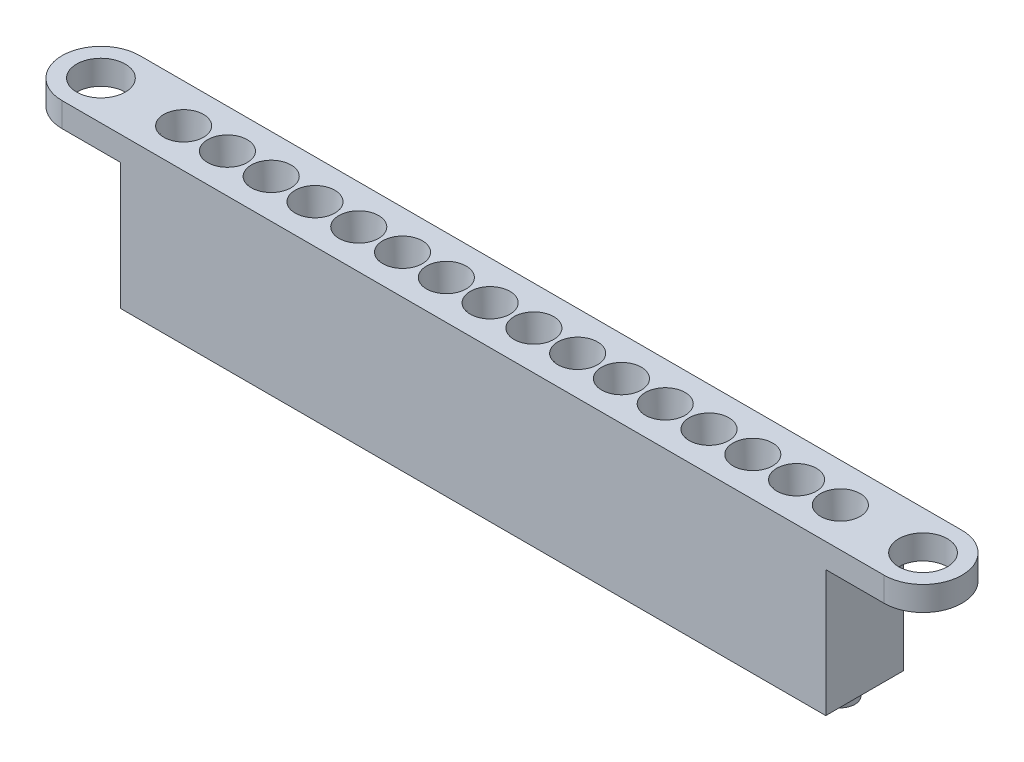
SolidWorks part; units mm, degrees
material "AISI 316 Stainless Steel Sheet (SS)"
ref_plane "Front" through (0, 0, 0) normal (0, 0, 1) x (1, 0, 0)
ref_plane "Top" through (0, 0, 0) normal (0, 1, 0) x (1, 0, 0)
ref_plane "Right" through (0, 0, 0) normal (1, 0, 0) x (0, 0, -1)
sketch "Sketch43" plane through (0, 0, 0) normal (0, 1, 0) x (1, 0, 0)
  line L0 (42.25, 0) -> (-42.25, 0) construction
  line L1 (42.25, -4) -> (-42.25, -4)
  line L2 (42.25, 4) -> (-42.25, 4)
  arc A0 (42.25, -4) -> (42.25, 4) centre (42.25, 0) ccw
  arc A1 (-42.25, 4) -> (-42.25, -4) centre (-42.25, 0) ccw
  circle A2 centre (-42.25, 0) radius 2.5
  circle A3 centre (42.25, 0) radius 2.5
  point P2 (0, 0)
  dimension "D3" = 5
  dimension "D1" = 84.5
  dimension "D2" = 8
extrude "Boss-Extrude6" add sketch "Sketch43" along normal blind 17
sketch "Sketch41" plane through (0, 0, 0) normal (0, 0, 1) x (1, 0, 0)
  line L0 (0, 2.2756) -> (0, 5.0724) construction
  line L1 (2.25, 0) -> (2.25, 17) construction
  line L2 (2.25, 0) -> (3.25, 0) construction
  line L3 (3.25, 0) -> (4.2898, 17)
  line L4 (4.2898, 17) -> (4.7898, 17) construction
  line L5 (4.7898, 17) -> (3.75, 0) construction
  line L6 (3.75, 0) -> (3.25, 0) construction
  line L7 (4.2898, 17) -> (2.25, 17)
  line L8 (2.25, 17) -> (2.25, 0)
  line L9 (2.25, 0) -> (3.25, 0)
  line L10 (-42.25, 17) -> (42.25, 17) construction
  dimension "D1" = 2.25
  dimension "D2" = 2
  dimension "D3" = 3
  dimension "D4" = 3.5
revolve "Cut-Revolve1" cut sketch "Sketch41" angle 360 about L8
pattern_linear "LPattern3" count 8 spacing 4.5 along (1, 0, 0) count 9 spacing 4.5 along (-1, 0, 0) of "Cut-Revolve1"
sketch "Sketch44" plane through (0, 0, 0) normal (0, 0, 1) x (1, 0, 0)
  line L0 (-42.25, 0) -> (42.25, 0) construction
  line L1 (-46.25, 14.5) -> (-36.25, 14.5)
  line L2 (-46.25, 14.5) -> (-46.25, 0)
  line L3 (-46.25, 0) -> (-36.25, 0)
  line L4 (-36.25, 14.5) -> (-36.25, 0)
  line L5 (-46.25, 17) -> (-46.25, 0) construction
  line L6 (-42.25, 17) -> (42.25, 17) construction
  line L7 (-39.75, 17) -> (-44.75, 17) construction
  line L8 (-39.75, 17) -> (-44.75, 17) construction
  line L9 (0, -4.7141) -> (0, -12.6187) construction
  line L10 (39.75, 17) -> (44.75, 17) construction
  line L11 (36.25, 14.5) -> (36.25, 0)
  line L12 (46.25, 0) -> (36.25, 0)
  line L13 (46.25, 14.5) -> (46.25, 0)
  line L14 (46.25, 14.5) -> (36.25, 14.5)
  point P12 (-42.25, 17)
  dimension "D1" = 2.5
  dimension "D2" = 6
extrude "Cut-Extrude13" cut sketch "Sketch44" against normal through all both and the other way through all
sketch "Sketch46" plane through (0, 0, 0) normal (0, 0, 1) x (1, 0, 0)
  line L0 (3.75, 0) -> (3.8417, 1.5)
  line L1 (4.7898, 17) -> (3.75, 0) construction
  line L2 (3.8417, 1.5) -> (4.25, 1.5)
  line L3 (4.25, 1.5) -> (4.25, 0)
  line L4 (-36.25, 0) -> (36.25, 0) construction
  line L5 (4.25, 0) -> (3.75, 0)
  line L6 (2.25, 17) -> (2.25, 0) construction
  line L7 (2.25, 17) -> (2.25, 0) construction
  dimension "D1" = 1.5
  dimension "D2" = 0.5
  dimension "D3" = 3.5
revolve "Cut-Revolve2" cut sketch "Sketch46" angle 360 about L7
pattern_linear "LPattern7" count 8 spacing 4.5 along (1, 0, 0) count 9 spacing 4.5 along (-1, 0, 0) of "Cut-Revolve2"
sketch "Sketch47" plane through (0, 0, 0) normal (0, 1, 0) x (1, 0, 0)
  line L0 (-36.25, 4) -> (-36.25, -4) construction
  line L1 (36.25, 4) -> (-36.25, 4) construction
  line L2 (36.25, 4) -> (36.25, -4) construction
  line L3 (-36.25, -4) -> (36.25, -4) construction
  line L4 (-36.25, 4) -> (-36.25, -4)
  line L5 (36.25, 4) -> (-36.25, 4)
  line L6 (36.25, 4) -> (36.25, -4)
  line L7 (-36.25, -4) -> (36.25, -4)
  circle A0 centre (-15.75, 0) radius 2 construction
  circle A1 centre (-20.25, 0) radius 2 construction
  circle A2 centre (-24.75, 0) radius 2 construction
  circle A3 centre (-29.25, 0) radius 2 construction
  circle A4 centre (-33.75, 0) radius 2 construction
  circle A5 centre (-15.75, 0) radius 2
  circle A6 centre (-20.25, 0) radius 2
  circle A7 centre (-24.75, 0) radius 2
  circle A8 centre (-29.25, 0) radius 2
  circle A9 centre (-33.75, 0) radius 2
  circle A10 centre (11.25, 0) radius 2 construction
  circle A11 centre (6.75, 0) radius 2 construction
  circle A12 centre (2.25, 0) radius 2 construction
  circle A13 centre (-2.25, 0) radius 2 construction
  circle A14 centre (-6.75, 0) radius 2 construction
  circle A15 centre (-11.25, 0) radius 2 construction
  circle A16 centre (11.25, 0) radius 2
  circle A17 centre (6.75, 0) radius 2
  circle A18 centre (2.25, 0) radius 2
  circle A19 centre (-2.25, 0) radius 2
  circle A20 centre (-6.75, 0) radius 2
  circle A21 centre (-11.25, 0) radius 2
  circle A22 centre (33.75, 0) radius 2 construction
  circle A23 centre (29.25, 0) radius 2 construction
  circle A24 centre (24.75, 0) radius 2 construction
  circle A25 centre (20.25, 0) radius 2 construction
  circle A26 centre (15.75, 0) radius 2 construction
  circle A27 centre (33.75, 0) radius 2
  circle A28 centre (29.25, 0) radius 2
  circle A29 centre (24.75, 0) radius 2
  circle A30 centre (20.25, 0) radius 2
  circle A31 centre (15.75, 0) radius 2
extrude "Cut-Extrude14" cut sketch "Sketch47" along normal up to surface (1.5 mm away) up to face at (-3.8417, 1.5, 0)
sketch "Sketch42" plane through (0, 0, 0) normal (0, 0, 1) x (1, 0, 0)
  line L0 (2.25, 0) -> (2.25, 17) construction
  line L1 (2.25, 0) -> (2.25, 17) construction
  line L2 (3.25, 0) -> (4.2898, 17) construction
  line L3 (3.25, 0) -> (4.2898, 17)
  line L4 (3.25, 0) -> (2.25, 0)
  line L5 (2.25, 17) -> (4.2898, 17)
  line L6 (2.25, 0) -> (2.25, 17)
revolve "Well Volume" [suppressed] add sketch "Sketch42" angle 360 about L1
sketch "stock" plane through (0, 0, 0) normal (0, -1, 0) x (1, 0, 0)
  line L4 (-36.25, 4) -> (-36.25, -4)
  line L5 (-36.25, -4) -> (36.25, -4)
  line L6 (36.25, -4) -> (36.25, 4)
  line L7 (36.25, 4) -> (-36.25, 4)
  line L8 (-36.25, 4) -> (-36.25, -4)
  line L9 (-36.25, -4) -> (36.25, -4)
  line L10 (36.25, -4) -> (36.25, 4)
  line L11 (36.25, 4) -> (-36.25, 4)
  circle A0 centre (-33.75, 0) radius 0.7874
  dimension "D2" = 1.5748
  dimension "D1" = 0
ref_plane "Plane1" through (0, -25.4, 0) normal (0, -1, 0) x (-1, 0, 0)
sketch "Zero" plane through (0, -25.4, 0) normal (0, -1, 0) x (-1, 0, 0)
  circle A0 centre (33.75, 0) radius 1 construction
  circle A1 centre (33.75, 0) radius 1
ref_plane "Plane for Wire" through (0, 55.2778, 0) normal (0, 1, 0) x (1, 0, 0)
sketch "Zero new" plane through (0, 55.2778, 0) normal (0, 1, 0) x (1, 0, 0)
  circle A0 centre (-33.75, 0) radius 2.0398 construction
  circle A1 centre (-33.75, 0) radius 2.0398
sketch "stock new" plane through (0, 17, 0) normal (0, 1, 0) x (1, 0, 0)
  line L4 (-36.25, 4) -> (-36.25, -4)
  line L5 (36.25, 4) -> (-36.25, 4)
  line L6 (36.25, -4) -> (36.25, 4)
  line L7 (-36.25, -4) -> (36.25, -4)
  line L8 (-36.25, 4) -> (-36.25, -4)
  line L9 (36.25, 4) -> (-36.25, 4)
  line L10 (36.25, -4) -> (36.25, 4)
  line L11 (-36.25, -4) -> (36.25, -4)
  dimension "D1" = 0
sketch "Sketch48" plane through (0, 1.5, 0) normal (0, -1, 0) x (1, 0, 0)
  circle A0 centre (33.75, 0) radius 1.5917 construction
  circle A1 centre (29.25, 0) radius 1.5917 construction
  circle A2 centre (24.75, 0) radius 1.5917 construction
  circle A3 centre (20.25, 0) radius 1.5917 construction
  circle A4 centre (15.75, 0) radius 1.5917 construction
  circle A5 centre (11.25, 0) radius 1.5917 construction
  circle A6 centre (6.75, 0) radius 1.5917 construction
  circle A7 centre (2.25, 0) radius 1.5917 construction
  circle A8 centre (-2.25, 0) radius 1.5917 construction
  circle A9 centre (-6.75, 0) radius 1.5917 construction
  circle A10 centre (-11.25, 0) radius 1.5917 construction
  circle A11 centre (-15.75, 0) radius 1.5917 construction
  circle A12 centre (-20.25, 0) radius 1.5917 construction
  circle A13 centre (-24.75, 0) radius 1.5917 construction
  circle A14 centre (-29.25, 0) radius 1.5917 construction
  circle A15 centre (-33.75, 0) radius 1.5917 construction
  circle A16 centre (33.75, 0) radius 1.5917
  circle A17 centre (29.25, 0) radius 1.5917
  circle A18 centre (24.75, 0) radius 1.5917
  circle A19 centre (20.25, 0) radius 1.5917
  circle A20 centre (15.75, 0) radius 1.5917
  circle A21 centre (11.25, 0) radius 1.5917
  circle A22 centre (6.75, 0) radius 1.5917
  circle A23 centre (2.25, 0) radius 1.5917
  circle A24 centre (-2.25, 0) radius 1.5917
  circle A25 centre (-6.75, 0) radius 1.5917
  circle A26 centre (-11.25, 0) radius 1.5917
  circle A27 centre (-15.75, 0) radius 1.5917
  circle A28 centre (-20.25, 0) radius 1.5917
  circle A29 centre (-24.75, 0) radius 1.5917
  circle A30 centre (-29.25, 0) radius 1.5917
  circle A31 centre (-33.75, 0) radius 1.5917
sketch "Sketch49" plane through (0, 1.5, 0) normal (0, -1, 0) x (1, 0, 0)
  arc A0 (-31.9091, 1.3553) -> (-31.9091, -1.3553) centre (-33.75, 0) ccw
  arc A1 (-31.0909, -1.3553) -> (-27.4091, -1.3553) centre (-29.25, 0) ccw
  arc A2 (-26.5909, -1.3553) -> (-22.975, -1.4405) centre (-24.75, 0) ccw
  arc A3 (-18.475, 1.4405) -> (-22.025, 1.4405) centre (-20.25, 0) ccw
  arc A4 (-13.975, 1.4405) -> (-17.525, 1.4405) centre (-15.75, 0) ccw
  arc A5 (-9.475, 1.4405) -> (-13.025, 1.4405) centre (-11.25, 0) ccw
  arc A6 (-4.975, 1.4405) -> (-8.525, 1.4405) centre (-6.75, 0) ccw
  arc A7 (-0.475, 1.4405) -> (-4.025, 1.4405) centre (-2.25, 0) ccw
  arc A8 (4.025, 1.4405) -> (0.475, 1.4405) centre (2.25, 0) ccw
  arc A9 (8.525, 1.4405) -> (4.975, 1.4405) centre (6.75, 0) ccw
  arc A10 (13.025, 1.4405) -> (9.475, 1.4405) centre (11.25, 0) ccw
  arc A11 (17.525, 1.4405) -> (13.975, 1.4405) centre (15.75, 0) ccw
  arc A12 (22.025, 1.4405) -> (18.475, 1.4405) centre (20.25, 0) ccw
  arc A13 (26.525, 1.4405) -> (22.975, 1.4405) centre (24.75, 0) ccw
  arc A14 (31.025, 1.4405) -> (27.475, 1.4405) centre (29.25, 0) ccw
  arc A15 (31.975, -1.4405) -> (31.975, 1.4405) centre (33.75, 0) ccw
  arc A16 (-31.0909, 1.3553) -> (-31.9091, 1.3553) centre (-31.5, 1.6565) cw
  arc A17 (-31.0909, -1.3553) -> (-31.9091, -1.3553) centre (-31.5, -1.6565) ccw
  arc A18 (27.475, -1.4405) -> (31.025, -1.4405) centre (29.25, 0) ccw
  arc A19 (22.975, -1.4405) -> (26.525, -1.4405) centre (24.75, 0) ccw
  arc A20 (18.475, -1.4405) -> (22.025, -1.4405) centre (20.25, 0) ccw
  arc A21 (13.975, -1.4405) -> (17.525, -1.4405) centre (15.75, 0) ccw
  arc A22 (9.475, -1.4405) -> (13.025, -1.4405) centre (11.25, 0) ccw
  arc A23 (4.975, -1.4405) -> (8.525, -1.4405) centre (6.75, 0) ccw
  arc A24 (0.475, -1.4405) -> (4.025, -1.4405) centre (2.25, 0) ccw
  arc A25 (-4.025, -1.4405) -> (-0.475, -1.4405) centre (-2.25, 0) ccw
  arc A26 (-8.525, -1.4405) -> (-4.975, -1.4405) centre (-6.75, 0) ccw
  arc A27 (-13.025, -1.4405) -> (-9.475, -1.4405) centre (-11.25, 0) ccw
  arc A28 (-17.525, -1.4405) -> (-13.975, -1.4405) centre (-15.75, 0) ccw
  arc A29 (-27.4091, 1.3553) -> (-31.0909, 1.3553) centre (-29.25, 0) ccw
  arc A30 (-27.4091, -1.3553) -> (-26.5909, -1.3553) centre (-27, -1.6565) cw
  arc A31 (-26.5909, 1.3553) -> (-27.4091, 1.3553) centre (-27, 1.6565) cw
  arc A32 (-22.025, -1.4405) -> (-18.475, -1.4405) centre (-20.25, 0) ccw
  arc A33 (-22.975, 1.4405) -> (-26.5909, 1.3553) centre (-24.75, 0) ccw
  arc A34 (31.975, 1.4405) -> (31.025, 1.4405) centre (31.5, 1.826) cw
  arc A35 (31.975, -1.4405) -> (31.025, -1.4405) centre (31.5, -1.826) ccw
  arc A36 (27.475, -1.4405) -> (26.525, -1.4405) centre (27, -1.826) ccw
  arc A37 (27.475, 1.4405) -> (26.525, 1.4405) centre (27, 1.826) cw
  arc A38 (22.975, 1.4405) -> (22.025, 1.4405) centre (22.5, 1.826) cw
  arc A39 (22.975, -1.4405) -> (22.025, -1.4405) centre (22.5, -1.826) ccw
  arc A40 (18.475, -1.4405) -> (17.525, -1.4405) centre (18, -1.826) ccw
  arc A41 (18.475, 1.4405) -> (17.525, 1.4405) centre (18, 1.826) cw
  arc A42 (13.975, 1.4405) -> (13.025, 1.4405) centre (13.5, 1.826) cw
  arc A43 (13.975, -1.4405) -> (13.025, -1.4405) centre (13.5, -1.826) ccw
  arc A44 (9.475, -1.4405) -> (8.525, -1.4405) centre (9, -1.826) ccw
  arc A45 (9.475, 1.4405) -> (8.525, 1.4405) centre (9, 1.826) cw
  arc A46 (4.975, 1.4405) -> (4.025, 1.4405) centre (4.5, 1.826) cw
  arc A47 (4.975, -1.4405) -> (4.025, -1.4405) centre (4.5, -1.826) ccw
  arc A48 (0.475, -1.4405) -> (-0.475, -1.4405) centre (0, -1.826) ccw
  arc A49 (0.475, 1.4405) -> (-0.475, 1.4405) centre (0, 1.826) cw
  arc A50 (-4.025, 1.4405) -> (-4.975, 1.4405) centre (-4.5, 1.826) cw
  arc A51 (-4.025, -1.4405) -> (-4.975, -1.4405) centre (-4.5, -1.826) ccw
  arc A52 (-8.525, -1.4405) -> (-9.475, -1.4405) centre (-9, -1.826) ccw
  arc A53 (-13.025, -1.4405) -> (-13.975, -1.4405) centre (-13.5, -1.826) ccw
  arc A54 (-8.525, 1.4405) -> (-9.475, 1.4405) centre (-9, 1.826) cw
  arc A55 (-13.025, 1.4405) -> (-13.975, 1.4405) centre (-13.5, 1.826) cw
  arc A56 (-17.525, 1.4405) -> (-18.475, 1.4405) centre (-18, 1.826) cw
  arc A57 (-17.525, -1.4405) -> (-18.475, -1.4405) centre (-18, -1.826) ccw
  arc A58 (-22.025, -1.4405) -> (-22.975, -1.4405) centre (-22.5, -1.826) ccw
  arc A59 (-22.025, 1.4405) -> (-22.975, 1.4405) centre (-22.5, 1.826) cw
  point P76 (27, -0.4041)
  point P85 (18, -0.4041)
  point P92 (13.5, -0.4041)
  point P95 (9, -0.4041)
  point P102 (4.5, -0.4041)
  point P105 (0, -0.4041)
  point P112 (-4.5, -0.4041)
  point P115 (-9, -0.4041)
  point P118 (-13.5, -0.4041)
  point P127 (-18, -0.4041)
  point P132 (-22.5, 0.4041)
  dimension "D1" = 4.572
  dimension "D2" = 4.572
  dimension "D3" = 4.572
  dimension "D4" = 4.572
  dimension "D5" = 4.572
  dimension "D6" = 4.572
  dimension "D7" = 4.572
  dimension "D8" = 4.572
  dimension "D9" = 4.572
  dimension "D10" = 4.572
  dimension "D11" = 4.572
  dimension "D12" = 4.572
  dimension "D13" = 4.572
  dimension "D14" = 4.572
  dimension "D15" = 4.572
  dimension "D16" = 4.572
  dimension "D17" = 0.508
  dimension "D18" = 0.508
  dimension "D19" = 0.508
  dimension "D20" = 0.6117
sketch "Fixture Clearance Slot" [suppressed] plane through (0, 17, 0) normal (0, 1, 0) x (1, 0, 0)
  line L0 (-42.25, 0) -> (42.25, 0) construction
  line L1 (-33.75, 0) -> (33.75, 0) construction
  line L2 (-33.75, 2.794) -> (33.75, 2.794)
  line L3 (-33.75, -2.794) -> (33.75, -2.794)
  line L4 (42.25, 4) -> (-42.25, 4) construction
  arc A0 (-33.75, 2.794) -> (-33.75, -2.794) centre (-33.75, 0) ccw
  arc A1 (33.75, -2.794) -> (33.75, 2.794) centre (33.75, 0) ccw
  point P6 (0, 0)
  dimension "D1" = 5.588
  dimension "D2" = 1.206
